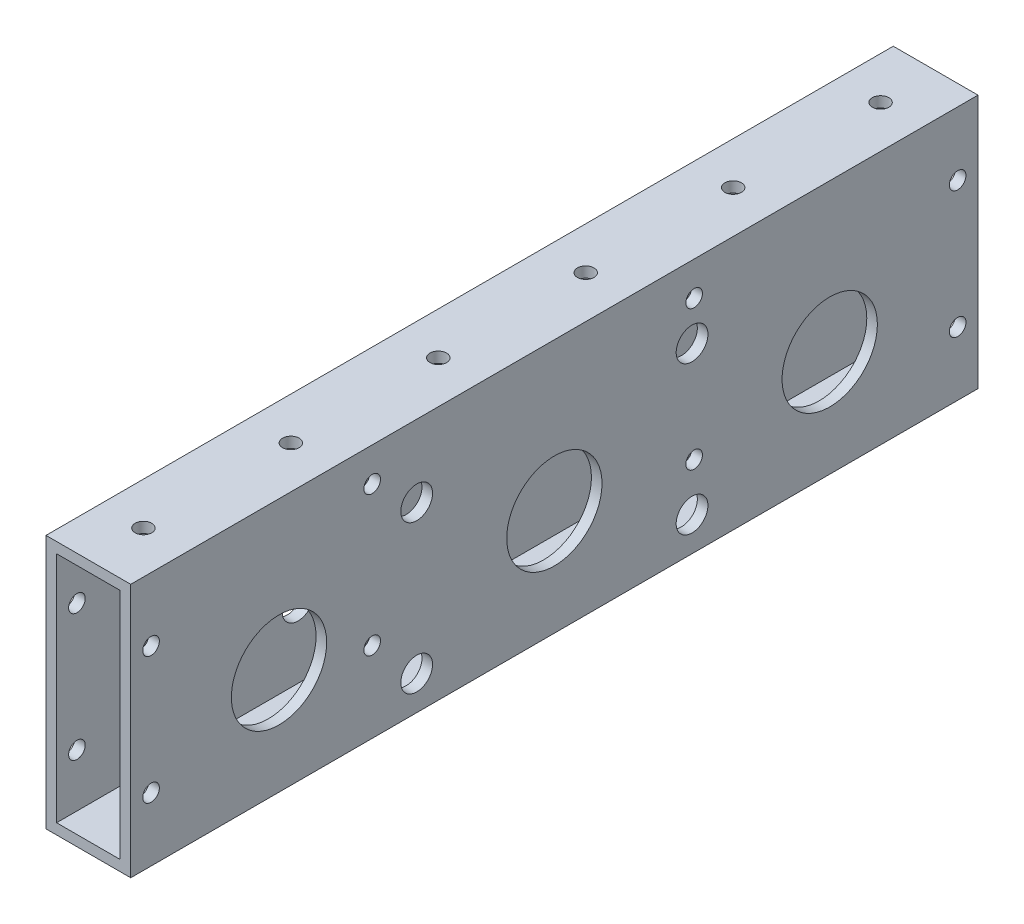
SolidWorks part; units mm, degrees
material "6061-T6 (SS)"
ref_plane "Front Plane" through (0, 0, 0) normal (0, 0, 1) x (1, 0, 0)
ref_plane "Top Plane" through (0, 0, 0) normal (0, 1, 0) x (1, 0, 0)
ref_plane "Right Plane" through (0, 0, 0) normal (1, 0, 0) x (0, 0, -1)
sketch "Sketch1" plane through (0, 0, 0) normal (1, 0, 0) x (0, 0, -1)
  line L1 (-127, 38.1) -> (127, 38.1)
  line L2 (-127, 38.1) -> (-127, -38.1)
  line L3 (-127, -38.1) -> (127, -38.1)
  line L4 (127, 38.1) -> (127, -38.1)
  line L5 (-127, 38.1) -> (127, -38.1) construction
  line L6 (-127, -38.1) -> (127, 38.1) construction
  point P0 (0, 0)
  dimension "D1" = 76.2
  dimension "D2" = 254
extrude "Boss-Extrude1" add sketch "Sketch1" along normal blind 25.4
shell "Shell1" thickness 3.175
sketch "Sketch2" plane through (25.4, 0, 0) normal (1, 0, 0) x (0, 0, -1)
  line L0 (-127, -38.1) -> (127, -38.1) construction
  line L1 (127, 38.1) -> (-127, 38.1) construction
  line L2 (-41.275, -27.94) -> (41.275, -27.94) construction
  line L3 (-41.275, -27.94) -> (-41.275, 16.51) construction
  line L4 (-41.275, 16.51) -> (41.275, 16.51) construction
  line L5 (41.275, -27.94) -> (41.275, 16.51) construction
  line L6 (-41.275, -27.94) -> (41.275, 16.51) construction
  line L7 (-41.275, 16.51) -> (41.275, -27.94) construction
  line L9 (-54.61, 27.94) -> (41.91, 27.94) construction
  line L10 (-54.61, 27.94) -> (-54.61, -13.97) construction
  line L11 (-54.61, -13.97) -> (41.91, -13.97) construction
  line L12 (41.91, 27.94) -> (41.91, -13.97) construction
  circle A0 centre (0, -6.35) radius 14.2875
  circle A1 centre (-82.55, -6.35) radius 14.2875
  circle A2 centre (82.55, -6.35) radius 14.2875
  circle A3 centre (-82.55, -6.35) radius 38.1 construction
  circle A4 centre (0, -6.35) radius 38.1 construction
  circle A5 centre (82.55, -6.35) radius 38.1 construction
  circle A6 centre (-41.275, 16.51) radius 2.4892
  circle A7 centre (-41.275, -27.94) radius 2.4892
  circle A8 centre (41.275, -27.94) radius 2.4892
  circle A9 centre (41.275, 16.51) radius 2.4892
  circle A10 centre (-54.61, 27.94) radius 2.4892
  circle A11 centre (-54.61, -13.97) radius 2.4892
  circle A12 centre (41.91, -13.97) radius 2.4892
  circle A13 centre (41.91, 27.94) radius 2.4892
  point P11 (0, 0)
  point P12 (0, -5.715)
  dimension "D1" = 28.575
  dimension "D5" = 76.2
  dimension "D10" = 4.9784
  dimension "D2" = 31.75
  dimension "D3" = 82.55
  dimension "D4" = 82.55
  dimension "D6" = 0
  dimension "D7" = 10.16
  dimension "D8" = 21.59
  dimension "D9" = 82.55
  dimension "D11" = 10.16
  dimension "D12" = 96.52
  dimension "D13" = 41.91
  dimension "D14" = 24.13
extrude "Cut-Extrude1" cut sketch "Sketch2" against normal through all
sketch "Sketch3" plane through (25.4, 0, 0) normal (1, 0, 0) x (0, 0, -1)
  line L0 (-120.904, 19.05) -> (-120.904, -19.05) construction
  line L1 (-127, 38.1) -> (-127, -38.1) construction
  point P2 (-120.904, 0)
  point P3 (-127, 0)
  dimension "D1" = 38.1
  dimension "D2" = 6.096
hole_wizard "#10 Clearance Hole1" positions "Sketch4" profile "Sketch6" hole size "#10" standard "ANSI Inch" end condition through all
sketch "Sketch4" plane through (25.4, 0, 0) normal (1, 0, 0) x (0, 0, -1)
  point P0 (-120.904, 19.05)
  point P3 (-120.904, -19.05)
sketch "Sketch6" plane through (25.4, 19.05, 120.904) normal (0, 1, 0) x (0, 0, -1)
  line L0 (0, 0) -> (0, 25.4)
  line L1 (0, 25.4) -> (2.4892, 25.4)
  line L2 (2.4892, 25.4) -> (2.4892, 0)
  line L5 (2.4892, 0) -> (0, 0)
  line L11 (0, -6.35) -> (0, 107.95) construction
  dimension "Thru Hole Dia." = 4.9784
  dimension "Thru Hole Depth" = 25.4
mirror "Mirror1" about plane through (0, 0, 0) normal (0, 0, 1) of "#10 Clearance Hole1"
hole_wizard "3/8 (0.375) Diameter Hole1" positions "Sketch7" profile "Sketch8" hole size "3/8" standard "ANSI Inch"
sketch "Sketch7" plane through (0, 0, 0) normal (-1, 0, 0) x (0, 0, 1)
  point P0 (54.61, 27.94)
  point P3 (54.61, -13.97)
  point P6 (-41.91, -13.97)
  point P9 (-41.91, 27.94)
sketch "Sketch8" plane through (0, 27.94, 54.61) normal (0, 1, 0) x (0, 0, 1)
  line L0 (0, 0) -> (0, 13.7836)
  line L1 (0, 13.7836) -> (4.7625, 10.922)
  line L2 (4.7625, 10.922) -> (4.7625, 0)
  line L5 (4.7625, 0) -> (0, 0)
  line L10 (0, 13.7836) -> (-4.7625, 10.922) construction
  line L11 (0, -6.35) -> (0, 107.95) construction
  dimension "Hole Dia." = 9.525
  dimension "Hole Depth" = 10.922
  dimension "Drill Angle" = 118
hole_wizard "3/8 (0.375) Diameter Hole2" positions "Sketch9" profile "Sketch10" hole size "3/8" standard "ANSI Inch"
sketch "Sketch9" plane through (25.4, 0, 0) normal (1, 0, 0) x (0, 0, -1)
  point P0 (-41.275, 16.51)
  point P3 (-41.275, -27.94)
  point P6 (41.275, 16.51)
  point P9 (41.275, -27.94)
sketch "Sketch10" plane through (25.4, 16.51, 41.275) normal (0, 1, 0) x (0, 0, -1)
  line L0 (0, 0) -> (0, 13.7836)
  line L1 (0, 13.7836) -> (4.7625, 10.922)
  line L2 (4.7625, 10.922) -> (4.7625, 0)
  line L5 (4.7625, 0) -> (0, 0)
  line L10 (0, 13.7836) -> (-4.7625, 10.922) construction
  line L11 (0, -6.35) -> (0, 107.95) construction
  dimension "Hole Dia." = 9.525
  dimension "Hole Depth" = 10.922
  dimension "Drill Angle" = 118
sketch "Sketch11" plane through (0, -38.1, 0) normal (0, -1, 0) x (1, 0, 0)
  line L0 (25.4, -127) -> (0, -127) construction
  circle A0 centre (12.7, -110.49) radius 2.4892
  circle A1 centre (12.7, -66.294) radius 2.4892
  circle A2 centre (12.7, -22.098) radius 2.4892
  circle A3 centre (12.7, 22.098) radius 2.4892
  circle A4 centre (12.7, 66.294) radius 2.4892
  circle A5 centre (12.7, 110.49) radius 2.4892
  point P2 (12.7, -127)
  dimension "D2" = 4.9784
  dimension "D1" = 16.51
  dimension "D4" = 44.196
  dimension "D3" = 6
extrude "Cut-Extrude2" cut sketch "Sketch11" against normal through all
